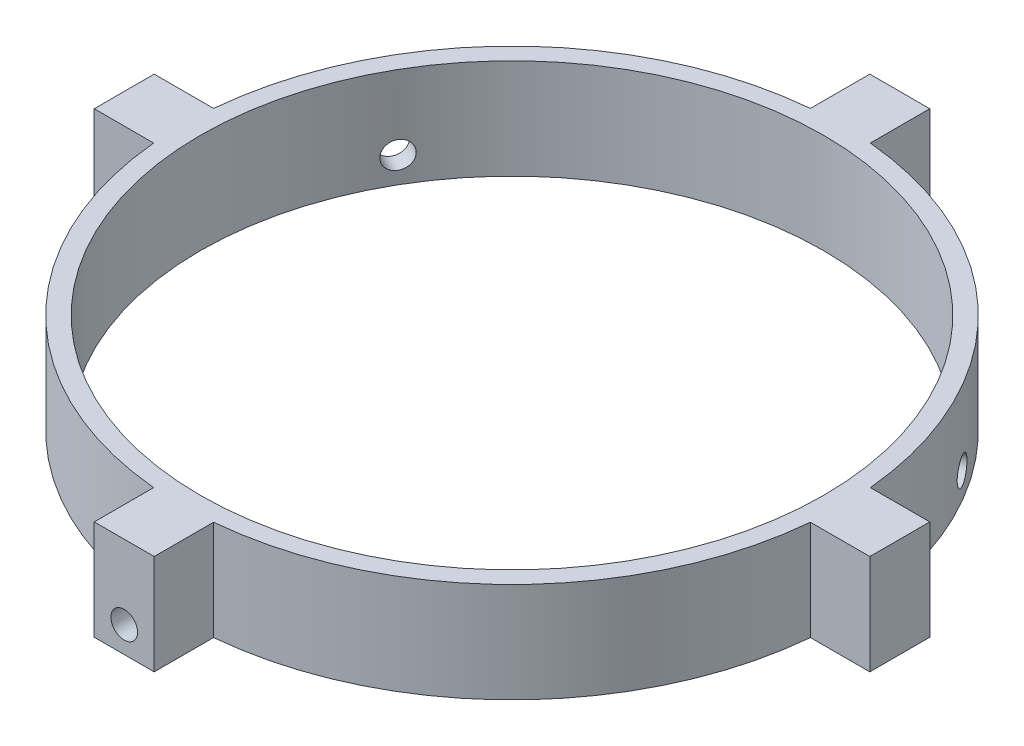
SolidWorks part; units mm, degrees
ref_plane "Front Plane" through (0, 0, 0) normal (0, 0, 1) x (1, 0, 0)
ref_plane "Top Plane" through (0, 0, 0) normal (0, 1, 0) x (1, 0, 0)
ref_plane "Right Plane" through (0, 0, 0) normal (1, 0, 0) x (0, 0, -1)
sketch "Sketch1" plane through (0, 0, 0) normal (0, 1, 0) x (1, 0, 0)
  circle A1 centre (0, 0) radius 42.9384
  circle A4 centre (0, 0) radius 39.624
extrude "Boss-Extrude1" add sketch "Sketch1" along normal blind 12.7 contours A1 A4
sketch "Sketch2" plane through (0, 0, 0) normal (0, 0, 1) x (1, 0, 0)
  line L1 (-42.9384, 12.7) -> (-49.2884, 12.7)
  line L5 (42.9384, 12.7) -> (-42.9384, 12.7) construction
  line L6 (-42.0241, 12.7) -> (-42.9384, 12.7)
  line L7 (-42.0241, 5.5435) -> (-49.2884, 12.7)
  line L8 (-42.0241, 12.7) -> (-42.0241, 5.5435)
sketch "Sketch4" plane through (0, 0, 0) normal (0, 0, 1) x (1, 0, 0)
  circle A0 centre (0, 3.2871) radius 1.6929
extrude "Cut-Extrude1" cut sketch "Sketch4" along normal blind 72.35
pattern_circular "CirPattern7" count 3 over 360 of "Cut-Extrude1"
sketch "Sketch6" plane through (0, 0, 0) normal (0, 0, 1) x (1, 0, 0)
  line L10 (0, 0) -> (0, 8.6868)
  line L14 (42.5405, 0) -> (49.2884, 0)
  line L15 (42.5405, 0) -> (42.5405, 12.7)
  line L16 (42.5405, 12.7) -> (49.2884, 12.7)
  line L17 (49.2884, 0) -> (49.2884, 12.7)
extrude "Boss-Extrude2" add sketch "Sketch6" along normal blind 3.81 and the other way blind 3.81 contours L15 L14 L17 L16
pattern_circular "CirPattern8" count 4 over 360 about axis through (0, 0, 0) along (0, 1, 0) of "Boss-Extrude2"
sketch "Sketch7" plane through (0, 0, 49.2884) normal (0, 0, 1) x (1, 0, 0)
  circle A0 centre (0, 3.2871) radius 1.6929
extrude "Cut-Extrude2" cut sketch "Sketch7" against normal blind 8.81
sketch "Sketch8" plane through (0, 12.7, 0) normal (0, 1, 0) x (1, 0, 0)
  line L0 (-42.769, 3.81) -> (-41.7365, 3.81)
  line L1 (-42.769, -3.81) -> (-41.7365, -3.81)
  line L2 (-3.81, -42.769) -> (-3.81, -41.7365)
  line L3 (3.81, -42.769) -> (3.81, -41.7365)
  line L4 (42.769, -3.81) -> (41.7365, -3.81)
  line L5 (42.769, 3.81) -> (41.7365, 3.81)
  line L6 (3.81, 42.769) -> (3.81, 41.7365)
  line L7 (-3.81, 42.769) -> (-3.81, 41.7365)
  circle A1 centre (0, 0) radius 41.91
  circle A2 centre (0, 0) radius 42.9384
extrude "Cut-Extrude3" cut sketch "Sketch8" against normal blind 24
sketch "Sketch10" plane through (0, 12.7, 0) normal (0, 1, 0) x (1, 0, 0)
  circle A0 centre (0, 0) radius 40.386
